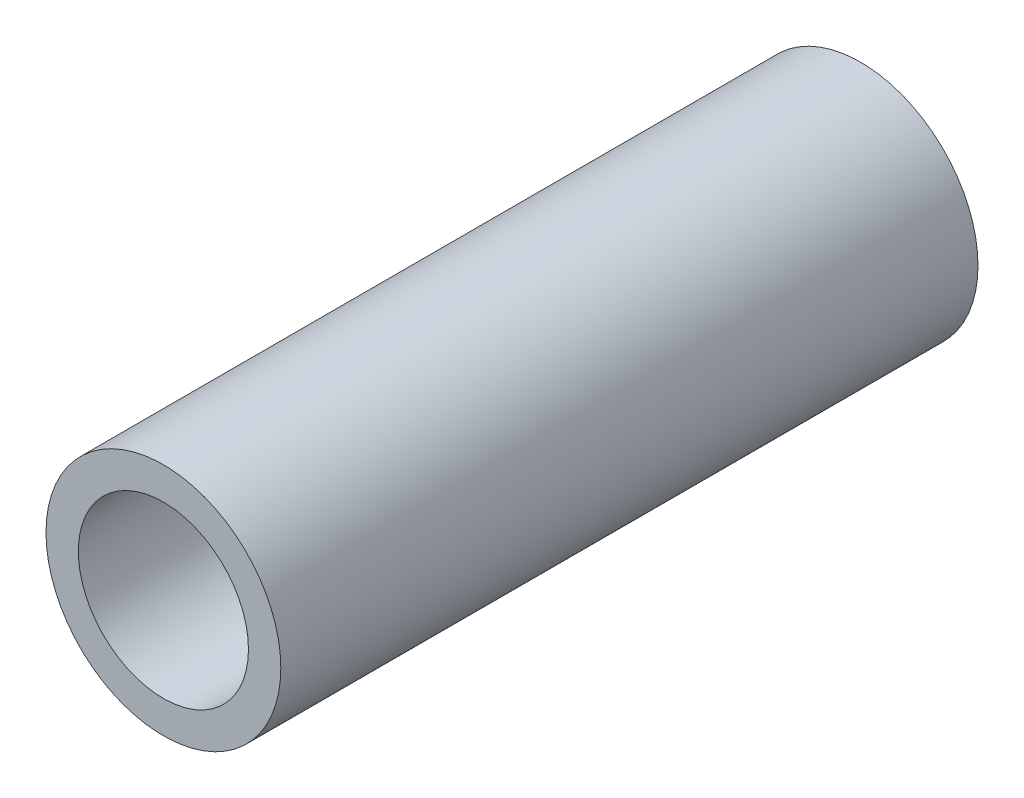
SolidWorks part; units mm, degrees
ref_plane "Front Plane" through (0, 0, 0) normal (0, 0, 1) x (1, 0, 0)
ref_plane "Top Plane" through (0, 0, 0) normal (0, 1, 0) x (1, 0, 0)
ref_plane "Right Plane" through (0, 0, 0) normal (1, 0, 0) x (0, 0, -1)
sketch "Sketch1" plane through (0, 0, 0) normal (0, 0, 1) x (1, 0, 0)
  circle A0 centre (0, 0) radius 10.6934
  circle A1 centre (0, 0) radius 7.747
  dimension "D1" = 21.3868
  dimension "D2" = 15.494
extrude "Boss-Extrude1" add sketch "Sketch1" along normal blind 63.5
